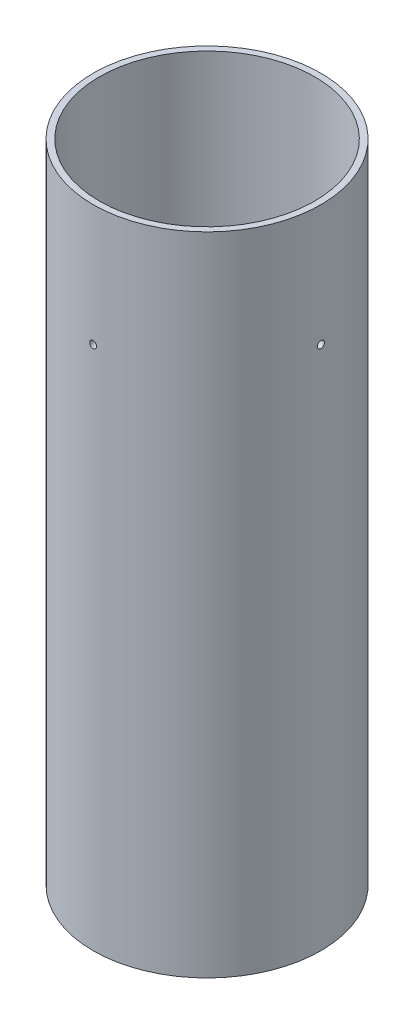
SolidWorks part; units mm, degrees
ref_plane "Front Plane" through (0, 0, 0) normal (0, 0, 1) x (1, 0, 0)
ref_plane "Top Plane" through (0, 0, 0) normal (0, 1, 0) x (1, 0, 0)
ref_plane "Right Plane" through (0, 0, 0) normal (1, 0, 0) x (0, 0, -1)
sketch "Sketch1" plane through (0, 0, 0) normal (0, 1, 0) x (1, 0, 0)
  circle A0 centre (0, 0) radius 50.8
  circle A1 centre (0, 0) radius 53.721
  dimension "D1" = 101.6
  dimension "D2" = 107.442
extrude "Tube Extrusion" add sketch "Sketch1" along normal blind 304.8
ref_plane "Plane1" through (53.721, 0, 0) normal (1, 0, 0) x (0, 0, -1)
sketch "Sketch2" plane through (53.721, 0, 0) normal (1, 0, 0) x (0, 0, -1)
  line L0 (0, 304.8) -> (0, 0) construction
  line L1 (50.8, 304.8) -> (-50.8, 304.8) construction
  circle A0 centre (0, 247.65) radius 1.6383
  dimension "D1" = 3.2766
  dimension "D2" = 247.65
extrude "Cut-Extrude1" cut sketch "Sketch2" against normal up to next
pattern_circular "CirPattern1" count 4 over 360 about axis through (0, 304.8, 0) along (0, -1, 0) of "Cut-Extrude1"
